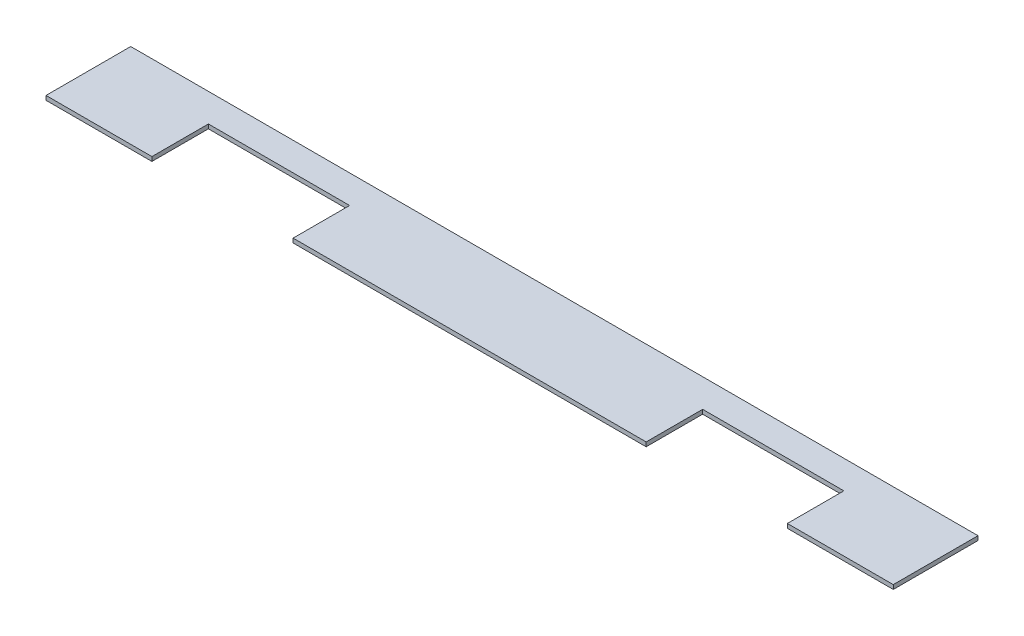
SolidWorks part; units mm, degrees
ref_plane "Front Plane" through (0, 0, 0) normal (0, 0, 1) x (1, 0, 0)
ref_plane "Top Plane" through (0, 0, 0) normal (0, 1, 0) x (1, 0, 0)
ref_plane "Right Plane" through (0, 0, 0) normal (1, 0, 0) x (0, 0, -1)
sketch "Sketch1" plane through (0, 0, 0) normal (0, 1, 0) x (1, 0, 0)
  line L1 (-300, 30) -> (300, 30)
  line L2 (-300, 30) -> (-300, -30)
  line L3 (-300, -30) -> (300, -30)
  line L4 (300, 30) -> (300, -30)
  line L5 (-300, 30) -> (300, -30) construction
  line L6 (-300, -30) -> (300, 30) construction
  point P0 (0, 0)
  dimension "D1" = 600
  dimension "D2" = 60
extrude "Boss-Extrude1" add sketch "Sketch1" along normal blind 3
sketch "Sketch2" plane through (0, 3, 0) normal (0, 1, 0) x (1, 0, 0)
  line L0 (-300, -30) -> (300, -30) construction
  line L1 (-225, -30) -> (-125, -30)
  line L2 (-225, -30) -> (-225, 10)
  line L3 (-225, 10) -> (-125, 10)
  line L4 (-125, -30) -> (-125, 10)
  line L5 (-300, 30) -> (-300, -30) construction
  line L6 (125, -30) -> (225, -30)
  line L7 (125, -30) -> (125, 10)
  line L8 (125, 10) -> (225, 10)
  line L9 (225, -30) -> (225, 10)
  line L10 (300, -30) -> (300, 30) construction
  dimension "D1" = 75
  dimension "D2" = 75
  dimension "D3" = 40
  dimension "D4" = 40
  dimension "D5" = 100
  dimension "D6" = 100
extrude "Cut-Extrude1" cut sketch "Sketch2" against normal blind 10
